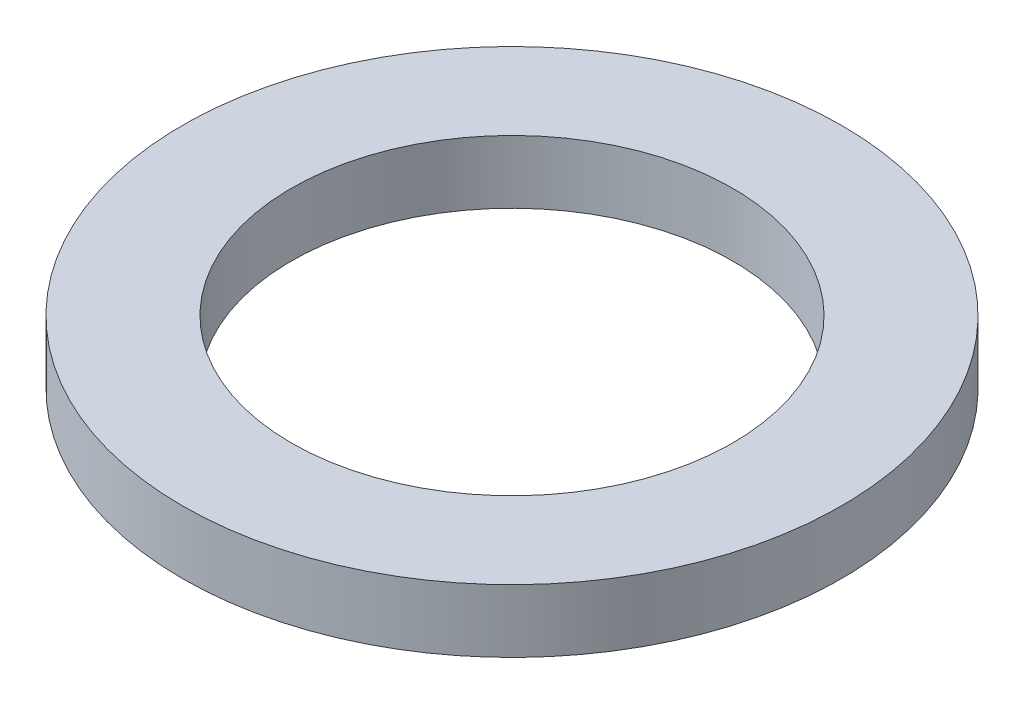
SolidWorks part; units mm, degrees
ref_plane "Front Plane" through (0, 0, 0) normal (0, 0, 1) x (1, 0, 0)
ref_plane "Top Plane" through (0, 0, 0) normal (0, 1, 0) x (1, 0, 0)
ref_plane "Right Plane" through (0, 0, 0) normal (1, 0, 0) x (0, 0, -1)
sketch "Sketch1" plane through (0, 0, 0) normal (0, 1, 0) x (1, 0, 0)
  circle A0 centre (0, 0) radius 11.5
  circle A1 centre (0, 0) radius 7.7
  dimension "D1" = 15.4
  dimension "D2" = 23
extrude "Boss-Extrude1" add sketch "Sketch1" along normal blind 2.2
